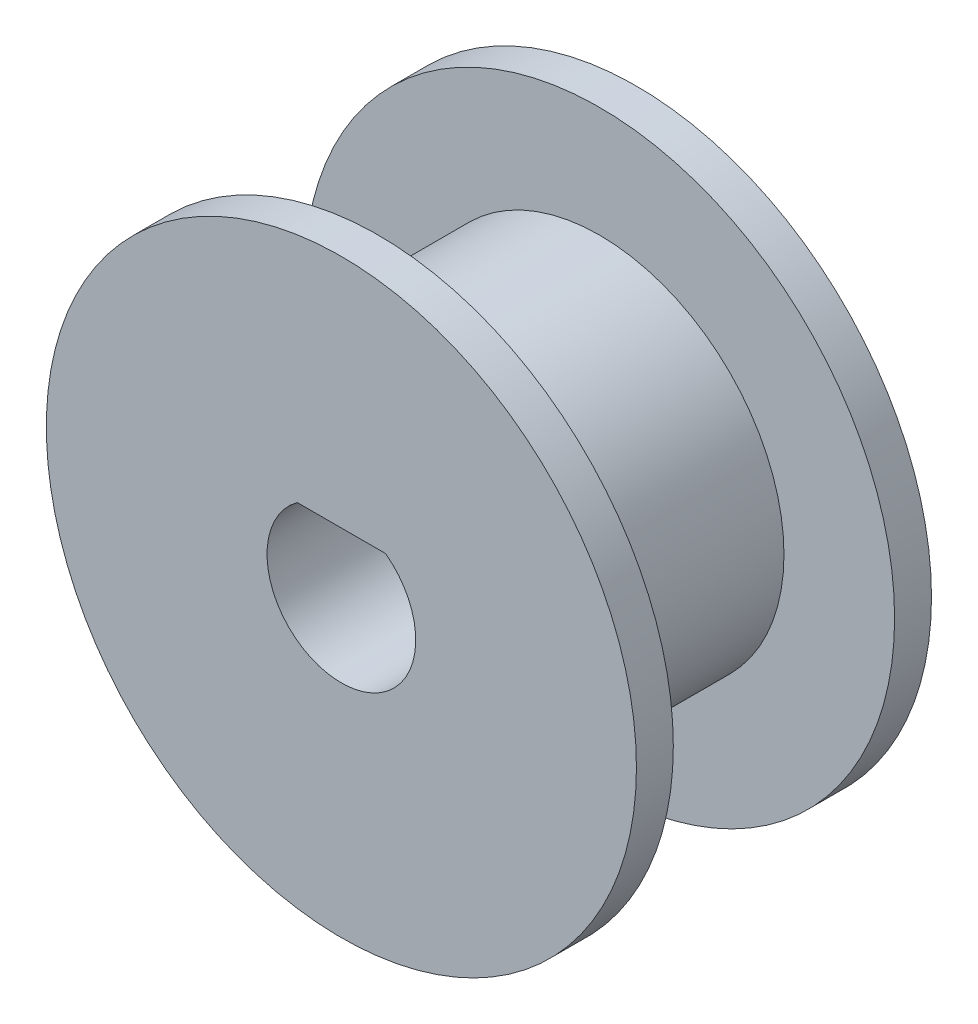
SolidWorks part; units mm, degrees
ref_plane "Front Plane" through (0, 0, 0) normal (0, 0, 1) x (1, 0, 0)
ref_plane "Top Plane" through (0, 0, 0) normal (0, 1, 0) x (1, 0, 0)
ref_plane "Right Plane" through (0, 0, 0) normal (1, 0, 0) x (0, 0, -1)
sketch "Sketch1" plane through (0, 0, 0) normal (0, 0, 1) x (1, 0, 0)
  circle A0 centre (0, 0) radius 12.7
  dimension "D1" = 25.4
extrude "base_volume" add sketch "Sketch1" along normal mid plane 12.7
sketch "Sketch2" plane through (0, 0, 0) normal (0, 0, 1) x (1, 0, 0)
  circle A0 centre (0, 0) radius 7.9375
  dimension "D1" = 15.875
extrude "encavure" cut sketch "Sketch2" against normal mid plane 9.525 flip side to cut
sketch "Sketch3" plane through (0, 0, 0) normal (0, 0, 1) x (1, 0, 0)
  line L0 (-1.9, 2.5749) -> (1.9, 2.5749)
  arc A0 (-1.9, 2.5749) -> (1.9, 2.5749) centre (0, 0) ccw
  dimension "D1" = 6.4
  dimension "D2" = 3.8
extrude "trou_shaft_D" cut sketch "Sketch3" against normal through all both and the other way through all
